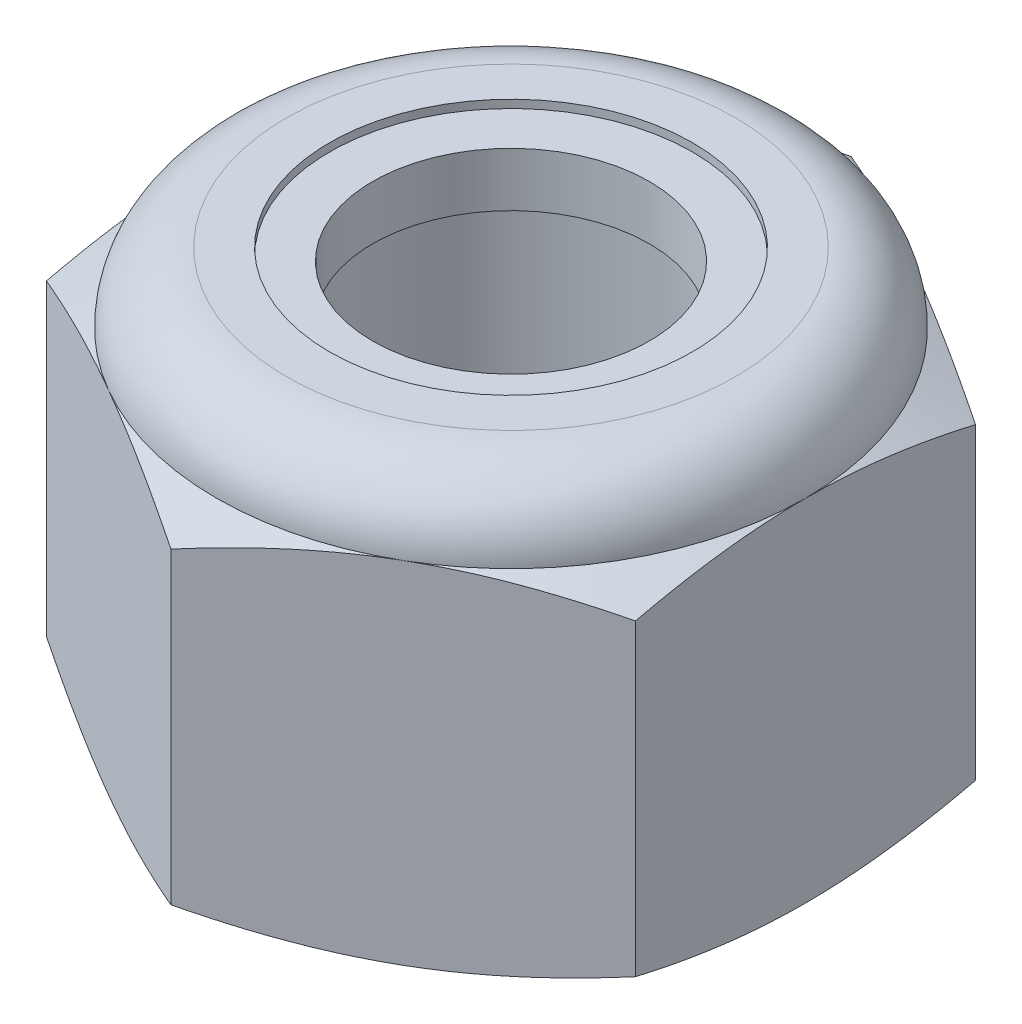
SolidWorks part; units mm, degrees
material "AISI 304"
ref_plane "Front" through (0, 0, 0) normal (0, 0, 1) x (1, 0, 0)
ref_plane "Top" through (0, 0, 0) normal (0, 1, 0) x (1, 0, 0)
ref_plane "Right" through (0, 0, 0) normal (1, 0, 0) x (0, 0, -1)
sketch "Sketch1" plane through (0, 0, 0) normal (0, 1, 0) x (1, 0, 0)
  line L1 (0, 6.4158) -> (-5.5563, 3.2079)
  line L2 (-5.5563, 3.2079) -> (-5.5563, -3.2079)
  line L3 (-5.5563, -3.2079) -> (0, -6.4158)
  line L4 (0, -6.4158) -> (5.5562, -3.2079)
  line L5 (5.5562, -3.2079) -> (5.5562, 3.2079)
  line L6 (5.5562, 3.2079) -> (0, 6.4158)
  circle A0 centre (0, 0) radius 5.5563 construction
  dimension "Hex Flats" = 11.1125
extrude "Extrude1" add sketch "Sketch1" along normal blind 7.9375
sketch "Sketch2" plane through (0, 0, 0) normal (1, 0, 0) x (0, 0, -1)
  line L0 (-3.175, 0) -> (-3.175, 7.9375) construction
  line L1 (0, 0) -> (3.175, 0)
  line L2 (0, 0) -> (0, 7.9375)
  line L3 (0, 7.9375) -> (3.175, 7.9375)
  line L4 (3.175, 0) -> (3.175, 7.9375)
  line L5 (-3.2079, 7.9375) -> (3.2079, 7.9375) construction
  line L7 (0, -3.175) -> (0, 0) construction
  dimension "Thread Dia" = 6.35
revolve "Revolve1" add sketch "Sketch2" angle 360 about L7
sketch "Sketch3" plane through (0, 0, 0) normal (1, 0, 0) x (0, 0, -1)
  line L0 (3.175, 7.9375) -> (-3.175, 7.9375) construction
  line L1 (-3.175, 7.9375) -> (-3.175, 6.6675) construction
  line L2 (-3.175, 6.6675) -> (3.175, 7.9375) construction
  line L3 (3.175, 7.9375) -> (3.2061, 7.7818) construction
  line L4 (3.2061, 7.7818) -> (3.4241, 6.6922)
  line L5 (3.4241, 6.6922) -> (2.6722, 6.9465)
  line L6 (2.6722, 6.9465) -> (2.6099, 7.2579)
  line L7 (2.6099, 7.2579) -> (3.2061, 7.7818)
  line L8 (2.641, 7.1022) -> (3.3151, 7.237) construction
  line L9 (3.175, 7.9375) -> (3.175, 7.209) construction
  line L10 (3.175, 7.209) -> (-3.175, 5.939) construction
  line L11 (-3.175, 5.939) -> (-3.175, 6.6675) construction
  line L12 (-0.2727, 7.9375) -> (0.2727, 5.2105) construction
  line L13 (-3.175, 0) -> (-3.175, 7.9375) construction
  line L14 (0, 7.9375) -> (3.175, 7.9375) construction
  line L15 (3.175, 0) -> (3.175, 7.9375) construction
  point P13 (0, 6.574)
  dimension "D1" = 0.1588
  dimension "D2" = 0.3175
  dimension "Thread Pitch" = 1.27
  dimension "D4" = 60
  dimension "D5" = 1.27
revolve "Cut-Revolve1" [suppressed] cut sketch "Sketch3" angle 360 about L12
pattern_linear "LPattern1" [suppressed] count 6 spacing 1.27 along (0, 1, 0) count 2 spacing 1.27 along (0, 1, 0)
sketch "Sketch4" plane through (0, 0, 0) normal (1, 0, 0) x (0, 0, -1)
  line L0 (0, 7.9375) -> (3.175, 7.9375)
  line L1 (3.175, 7.9375) -> (2.6099, 7.674)
  line L2 (2.6099, 7.674) -> (2.6099, 0.2635)
  line L3 (2.6099, 0.2635) -> (3.175, 0)
  line L4 (3.175, 0) -> (0, 0)
  line L5 (0, 0) -> (0, 7.9375)
  line L6 (3.175, 0) -> (3.175, 7.9375) construction
  line L7 (0, 7.9375) -> (3.175, 7.9375) construction
  line L8 (0, 0) -> (3.175, 0) construction
  line L9 (0, 0) -> (0, 7.9375) construction
  line L10 (0, 7.9375) -> (0, 8.561) construction
  dimension "D1" = 25
revolve "Cut-Revolve2" cut sketch "Sketch4" angle 360 about L10
combine bodies "Combine1" operation type subtract main body 112 bodies to subtract 109
sketch "Sketch5" plane through (0, 0, 0) normal (1, 0, 0) x (0, 0, -1)
  line L0 (0, 0) -> (5.5563, 0)
  line L1 (5.5563, 0) -> (6.4158, 0.4008)
  line L2 (6.4158, 0.4008) -> (6.4158, 6.2138)
  line L3 (6.4158, 6.2138) -> (5.5563, 6.6146)
  line L4 (4.2333, 7.9375) -> (4.2333, 9.2075)
  line L5 (4.2333, 9.2075) -> (7.6858, 9.2075)
  line L6 (7.6858, 9.2075) -> (7.6858, -1.27)
  line L7 (7.6858, -1.27) -> (0, -1.27)
  line L8 (0, -1.27) -> (0, 0)
  line L9 (5.5563, 6.6146) -> (5.5563, 0) construction
  line L10 (0, 0) -> (3.175, 0) construction
  line L13 (6.4158, 3.3073) -> (7.6858, 3.3073) construction
  line L14 (6.4158, 7.9375) -> (6.4158, 0) construction
  line L15 (0, 0) -> (0, 9.2075) construction
  line L20 (0, 9.2075) -> (4.2333, 9.2075) construction
  line L22 (0, 7.9375) -> (3.175, 7.9375) construction
  arc A0 (5.5563, 6.6146) -> (4.2333, 7.9375) centre (4.2333, 6.6146) ccw
  dimension "D1" = 25
  dimension "D2" = 1.27
  dimension "D3" = 7.9375
  dimension "D4" = 1.3229
revolve "Cut-Revolve3" cut sketch "Sketch5" angle 360 about L15
sketch "Sketch6" plane through (0, 0, 0) normal (1, 0, 0) x (0, 0, -1)
  line L0 (0, 6.6146) -> (5.4039, 6.6146)
  line L1 (4.2333, 7.7851) -> (3.4216, 7.7851)
  line L2 (0, 9.2075) -> (0, 6.6146)
  line L3 (3.4216, 9.2075) -> (0, 9.2075)
  line L4 (0, 9.2075) -> (4.2333, 9.2075) construction
  line L5 (0, 0) -> (0, 9.2075) construction
  line L6 (0, 9.2075) -> (0, 44.323) construction
  line L7 (3.4216, 7.7851) -> (3.4216, 9.2075)
  line L8 (4.2333, 7.9375) -> (4.2333, 7.7851) construction
  line L9 (3.4216, 7.7851) -> (2.6099, 7.7851) construction
  line L10 (2.6099, 7.7851) -> (2.6099, 7.674) construction
  arc A0 (5.4039, 6.6146) -> (4.2333, 7.7851) centre (4.2333, 6.6146) ccw
  arc A1 (5.5563, 6.6146) -> (4.2333, 7.9375) centre (4.2333, 6.6146) ccw construction
  dimension "D1" = 0.1524
revolve "Cut-Revolve4" cut sketch "Sketch6" angle 360 about L6
sketch "Sketch7" plane through (0, 0, 0) normal (1, 0, 0) x (0, 0, -1)
  line L0 (2.6099, 6.6908) -> (5.325, 6.6908)
  line L1 (4.2333, 7.7089) -> (2.6099, 7.7089)
  line L2 (2.6099, 7.7089) -> (2.6099, 6.6908)
  line L3 (2.6099, 6.6908) -> (0, 6.6908) construction
  line L4 (0, 6.6908) -> (0, 7.7089) construction
  line L5 (0, 7.7089) -> (2.6099, 7.7089) construction
  line L6 (2.6099, 6.6908) -> (2.6099, 6.6146) construction
  line L7 (0, 6.6146) -> (5.4039, 6.6146) construction
  line L8 (4.2333, 7.7089) -> (4.2333, 7.7851) construction
  arc A0 (5.325, 6.6908) -> (4.2333, 7.7089) centre (4.2333, 6.6146) ccw
  arc A2 (5.4039, 6.6146) -> (4.2333, 7.7851) centre (4.2333, 6.6146) ccw construction
  dimension "D1" = 0.0762
revolve "Revolve2" add sketch "Sketch7" angle 360 about L4
equation "\"D1@Sketch3\"=\"Thread Pitch@Sketch3\"/8"
equation "\"D2@Sketch3\"=\"Thread Pitch@Sketch3\"/4"
equation "\"D5@Sketch3\"=\"Thread Pitch@Sketch3\""
equation "\"D4@LPattern1\"=\"Thread Pitch@Sketch3\""
equation "\"D3@LPattern1\"=\"Thread Pitch@Sketch3\""
equation "\"D1@LPattern1\"=\"Height@Extrude1\"/\"Thread Pitch@Sketch3\""
equation "\"D4@Sketch5\"=\"Height@Extrude1\"/6"
